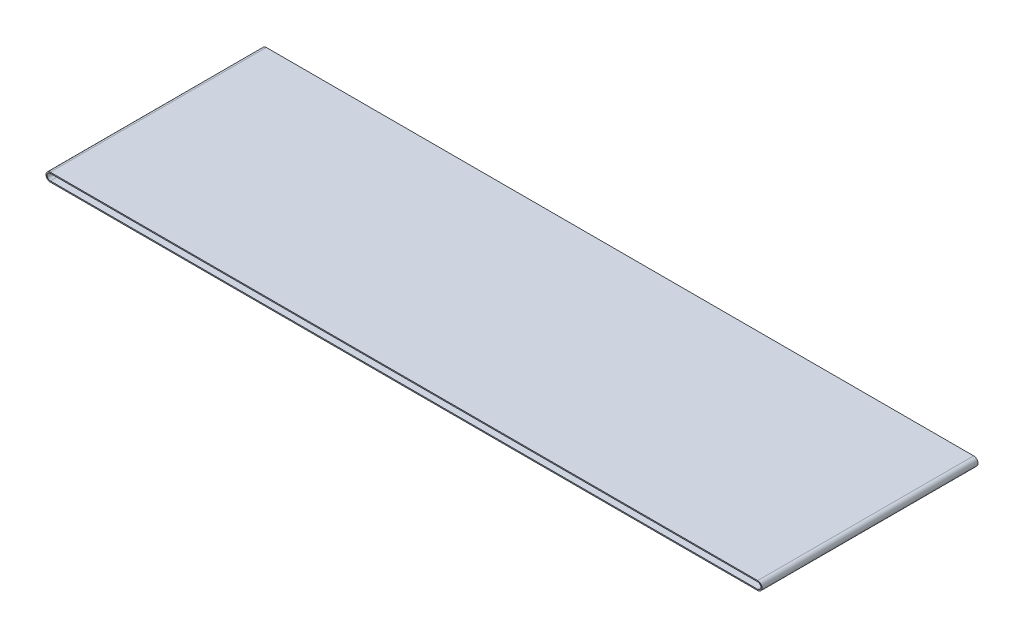
SolidWorks part; units mm, degrees
ref_plane "Front Plane" through (0, 0, 0) normal (0, 0, 1) x (1, 0, 0)
ref_plane "Top Plane" through (0, 0, 0) normal (0, 1, 0) x (1, 0, 0)
ref_plane "Right Plane" through (0, 0, 0) normal (1, 0, 0) x (0, 0, -1)
sketch "Sketch2" plane through (0, 0, 0) normal (0, 0, 1) x (1, 0, 0)
  line L0 (0, 0) -> (1, 0) construction
  line L1 (0, 0) -> (0, 1) construction
  line L2 (0, 3) -> (654.9676, 3)
  line L3 (654.9676, -3) -> (0, -3)
  arc A0 (0, -3) -> (0, 3) centre (0, 0) cw
  arc A1 (654.9676, 3) -> (654.9676, -3) centre (654.9676, 0) cw
extrude "Extrude-Thin1" add sketch "Sketch2" along normal mid plane 200 thin thin type one direction wall 1
